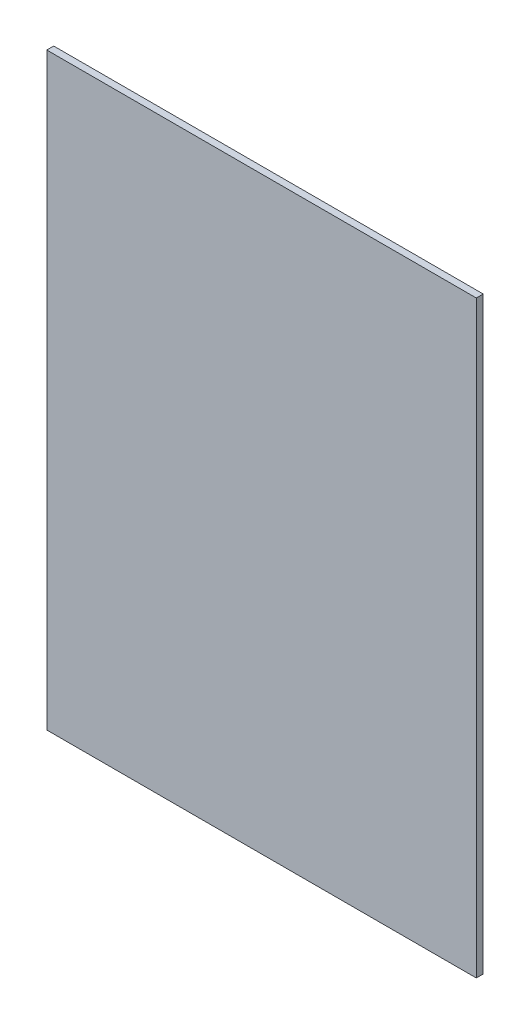
SolidWorks part; units mm, degrees
ref_plane "Front Plane" through (0, 0, 0) normal (0, 0, 1) x (1, 0, 0)
ref_plane "Top Plane" through (0, 0, 0) normal (0, 1, 0) x (1, 0, 0)
ref_plane "Right Plane" through (0, 0, 0) normal (1, 0, 0) x (0, 0, -1)
sketch "Sketch1" plane through (0, 0, 0) normal (0, 0, 1) x (1, 0, 0)
  line L1 (155, -212.5) -> (-155, -212.5)
  line L2 (155, -212.5) -> (155, 212.5)
  line L3 (155, 212.5) -> (-155, 212.5)
  line L4 (-155, -212.5) -> (-155, 212.5)
  line L5 (155, -212.5) -> (-155, 212.5) construction
  line L6 (155, 212.5) -> (-155, -212.5) construction
  point P0 (0, 0)
  dimension "D1" = 310
  dimension "D2" = 425
extrude "Boss-Extrude1" add sketch "Sketch1" along normal blind 5
